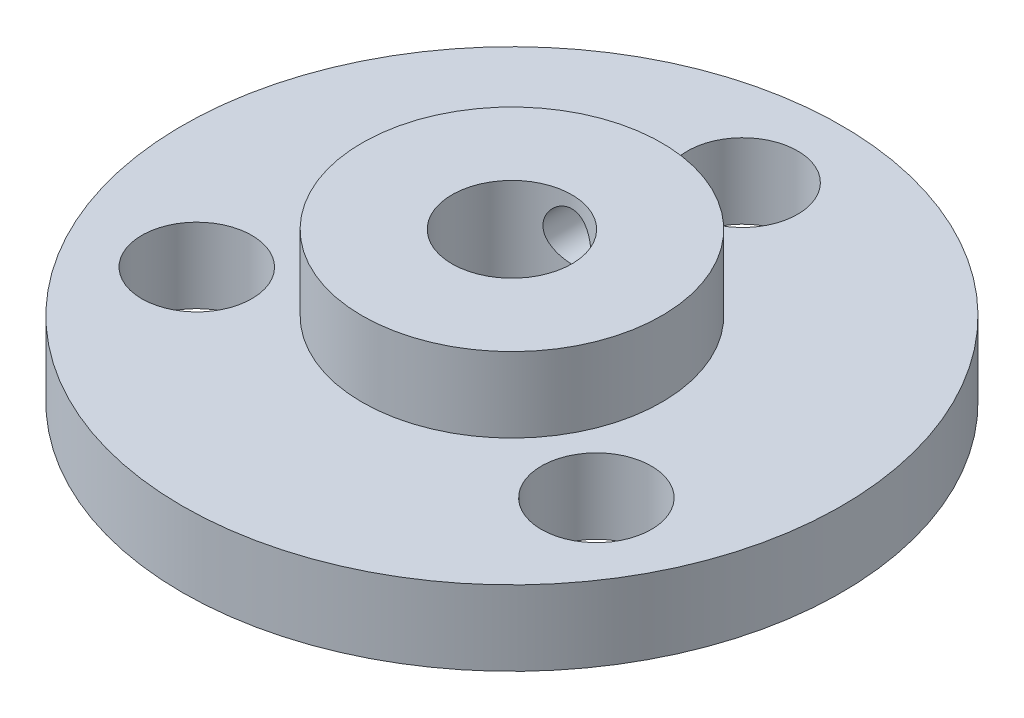
SolidWorks part; units mm, degrees
ref_plane "Plano frontal" through (0, 0, 0) normal (0, 0, 1) x (1, 0, 0)
ref_plane "Plano superior" through (0, 0, 0) normal (0, 1, 0) x (1, 0, 0)
ref_plane "Plano direito" through (0, 0, 0) normal (1, 0, 0) x (0, 0, -1)
sketch "Esboço1" plane through (0, 0, 0) normal (0, 1, 0) x (1, 0, 0)
  circle A0 centre (0, 0) radius 11
  dimension "D1" = 22
extrude "Ressalto-extrusão1" add sketch "Esboço1" along normal blind 2.5
sketch "Esboço3" plane through (0, 2.5, 0) normal (0, 1, 0) x (1, 0, 0)
  circle A1 centre (0, 7.7) radius 1.8355
  circle A2 centre (6.6684, -3.85) radius 1.8355
  circle A3 centre (-6.6684, -3.85) radius 1.8355
  dimension "D1" = 7.7
  dimension "D2" = 7.7
extrude "Corte-extrusão1" cut sketch "Esboço3" against normal blind 2.5
sketch "Esboço18" plane through (0, 2.5, 0) normal (0, 1, 0) x (1, 0, 0)
  circle A0 centre (0, 0) radius 5
  dimension "D1" = 10
extrude "Ressalto-extrusão5" add sketch "Esboço18" along normal blind 2.5
sketch "Esboço20" plane through (0, 5, 0) normal (0, 1, 0) x (1, 0, 0)
  circle A0 centre (0, 0) radius 2
  dimension "D1" = 4
extrude "Corte-extrusão5" cut sketch "Esboço20" against normal blind 5.5
hole_wizard "Broca de rosquear para tarraxa de M2x0.41" positions "3DSketch3" profile "Esboço21" hole size "M2x0.4" standard "Ansi Metric"
sketch3d "3DSketch3"
  point P0 (0.0026, 3.793, -5)
sketch "Esboço21" plane through (0.0026, 3.793, -5) normal (0, 1, 0) x (-1, 0, -0.0005)
  line L0 (0, 0) -> (0, 3)
  line L1 (0, 3) -> (0.8, 3)
  line L2 (0.8, 3) -> (0.8, 0)
  line L5 (0.8, 0) -> (0, 0)
  line L11 (0, -6.35) -> (0, 107.95) construction
  dimension "Thru Hole Dia." = 1.6
  dimension "Thru Hole Depth" = 3
